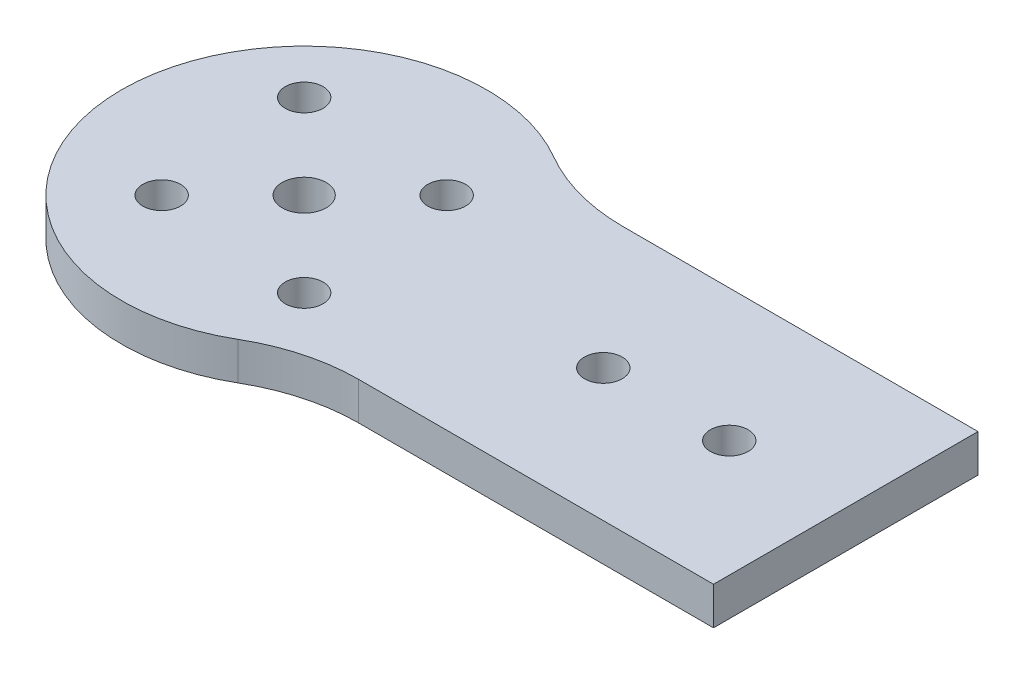
SolidWorks part; units mm, degrees
material "Hexcel AS4C (3000 Filaments)"
ref_plane "Front Plane" through (0, 0, 0) normal (0, 0, 1) x (1, 0, 0)
ref_plane "Top Plane" through (0, 0, 0) normal (0, 1, 0) x (1, 0, 0)
ref_plane "Right Plane" through (0, 0, 0) normal (1, 0, 0) x (0, 0, -1)
sketch "Sketch1" plane through (0, 0, 0) normal (0, 1, 0) x (1, 0, 0)
  line L0 (10, -10.5) -> (10, 10.5)
  line L1 (10, -10.5) -> (43, -10.5)
  line L2 (10, 10.5) -> (43, 10.5)
  line L3 (43, -10.5) -> (43, 10.5)
  line L4 (0, 0) -> (13.1288, 0)
  line L5 (0, 0) -> (0, 7.8507)
  line L6 (0, 0) -> (-6.7175, 6.7175)
  line L7 (0, 0) -> (5.6569, 5.6569)
  line L8 (0, 0) -> (-5.6569, -5.6569)
  line L9 (0, 0) -> (6.7175, -6.7175)
  circle A0 centre (0, 0) radius 14.5
  circle A1 centre (-6.7175, 6.7175) radius 1.5
  circle A2 centre (5.6569, 5.6569) radius 1.5
  circle A3 centre (-5.6569, -5.6569) radius 1.5
  circle A4 centre (6.7175, -6.7175) radius 1.5
  dimension "D1" = 29
  dimension "D9" = 3
  dimension "D10" = 3
  dimension "D15" = 3
  dimension "D16" = 3
  dimension "D2" = 21
  dimension "D3" = 33
  dimension "D4" = 13.1288
  dimension "D5" = 9.5
  dimension "D6" = 45
  dimension "D7" = 45
  dimension "D8" = 8
  dimension "D11" = 8
  dimension "D12" = 90
  dimension "D13" = 9.5
  dimension "D14" = 90
extrude "Boss-Extrude1" add sketch "Sketch1" along normal blind 3
fillet "Fillet1" radius 15 2 edges at (10, 1.5, -10.5) (10, 1.5, 10.5)
sketch "Sketch2" plane through (0, 3, 0) normal (0, 1, 0) x (1, 0, 0)
  line L0 (0, 0) -> (13.75, 0)
  line L1 (13.75, 0) -> (23.75, 0)
  line L2 (23.75, 0) -> (33.75, 0)
  circle A0 centre (0, 0) radius 13.75
  circle A1 centre (23.75, 0) radius 1.5
  circle A2 centre (33.75, 0) radius 1.5
  dimension "D1" = 27.5
  dimension "D4" = 3
  dimension "D5" = 3
  dimension "D2" = 10
  dimension "D3" = 10
extrude "Cut-Extrude1" cut sketch "Sketch2" against normal blind 3
sketch "Sketch3" plane through (0, 3, 0) normal (0, 1, 0) x (1, 0, 0)
  circle A0 centre (0, 0) radius 13.75
  dimension "D1" = 27.5
sketch "Sketch4" plane through (0, 3, 0) normal (0, 1, 0) x (1, 0, 0)
  circle A0 centre (0, 0) radius 1.75
  dimension "D1" = 3.5
extrude "Cut-Extrude2" cut sketch "Sketch4" against normal blind 10
